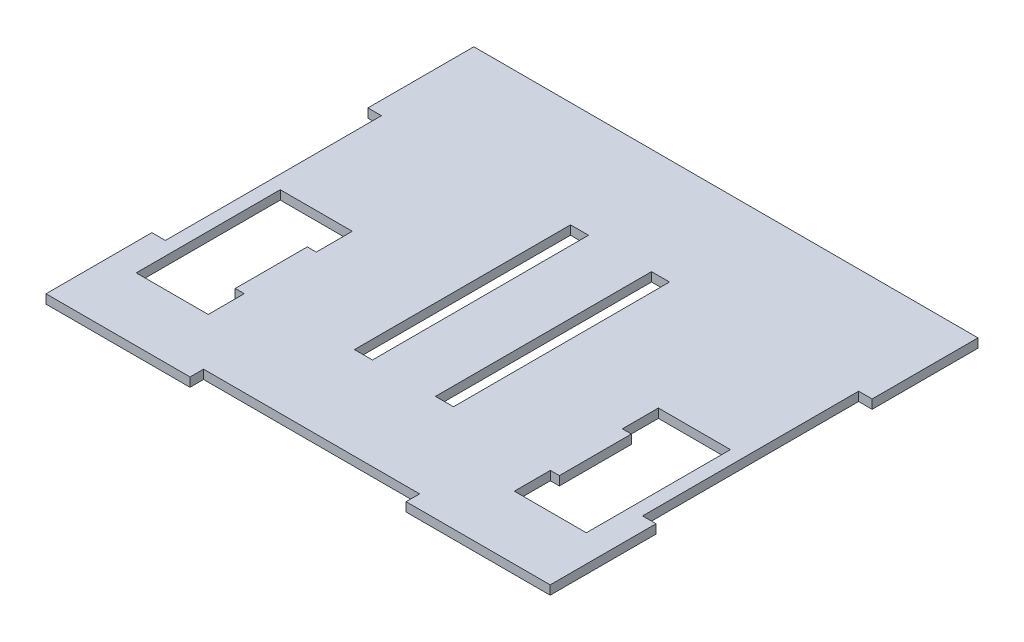
SolidWorks part; units mm, degrees
ref_plane "Front Plane" through (0, 0, 0) normal (0, 0, 1) x (1, 0, 0)
ref_plane "Top Plane" through (0, 0, 0) normal (0, 1, 0) x (1, 0, 0)
ref_plane "Right Plane" through (0, 0, 0) normal (1, 0, 0) x (0, 0, -1)
sketch "Sketch1" plane through (0, 0, 0) normal (0, 1, 0) x (1, 0, 0)
  line L1 (-177.8, -177.8) -> (-76.2, -177.8)
  line L2 (-177.8, -177.8) -> (-177.8, -103.124)
  line L4 (177.8, -177.8) -> (177.8, -103.124)
  line L5 (177.8, 123.952) -> (-177.8, 123.952)
  line L9 (-177.8, 49.276) -> (-168.275, 49.276)
  line L10 (177.8, 49.276) -> (168.275, 49.276)
  line L12 (177.8, -103.124) -> (168.275, -103.124)
  line L13 (168.275, 49.276) -> (168.275, -103.124)
  line L14 (-168.275, 49.276) -> (-168.275, -103.124)
  line L15 (-177.8, -103.124) -> (-168.275, -103.124)
  line L16 (177.8, 49.276) -> (177.8, 123.952)
  line L17 (-177.8, 49.276) -> (-177.8, 123.952)
  line L18 (76.2, -177.8) -> (177.8, -177.8)
  line L20 (76.2, -177.8) -> (76.2, -168.275)
  line L21 (76.2, -168.275) -> (-76.2, -168.275)
  line L22 (-76.2, -177.8) -> (-76.2, -168.275)
  point P0 (0, 0)
  point P16 (168.275, -26.924)
  point P25 (0, -168.275)
  dimension "D3" = 301.752
  dimension "D1" = 152.4
  dimension "D5" = 9.525
  dimension "D6" = 355.6
  dimension "D2" = 150.876
  dimension "D8" = 152.4
  dimension "D9" = 177.8
  dimension "D10" = 9.525
extrude "Boss-Extrude1" add sketch "Sketch1" along normal blind 6.35
sketch "Sketch4" plane through (0, 6.35, 0) normal (0, 1, 0) x (1, 0, 0)
  line L0 (158.75, -133.223) -> (158.75, -31.623)
  line L1 (158.75, -31.623) -> (120.65, -31.623)
  line L2 (120.65, -31.623) -> (120.65, -133.223)
  line L3 (120.65, -133.223) -> (158.75, -133.223)
  line L5 (0, -177.8) -> (0, 177.8) construction
  line L6 (123.952, 177.8) -> (-123.952, 177.8) construction
  line L7 (-120.65, -31.623) -> (-120.65, -133.223)
  line L8 (-158.75, -31.623) -> (-120.65, -31.623)
  line L9 (-158.75, -133.223) -> (-158.75, -31.623)
  line L10 (-120.65, -133.223) -> (-158.75, -133.223)
  dimension "D1" = 101.6
  dimension "D2" = 120.65
  dimension "D3" = 38.1
extrude "Cut-Extrude3" cut sketch "Sketch4" against normal through all
sketch "Sketch5" plane through (0, 6.35, 0) normal (0, 1, 0) x (1, 0, 0)
  line L0 (120.65, -133.223) -> (107.95, -133.223)
  line L1 (107.95, -133.223) -> (107.95, -107.823)
  line L2 (107.95, -107.823) -> (120.65, -107.823)
  line L3 (120.65, -31.623) -> (120.65, -133.223) construction
  line L4 (120.65, -107.823) -> (120.65, -133.223)
  line L5 (177.8, -177.8) -> (-177.8, -177.8) construction
  line L6 (0, -177.8) -> (0, 30.2394) construction
  line L7 (120.65, -31.623) -> (107.95, -31.623)
  line L8 (107.95, -31.623) -> (107.95, -57.023)
  line L9 (107.95, -57.023) -> (120.65, -57.023)
  line L10 (120.65, -57.023) -> (120.65, -31.623)
  line L11 (-107.95, -57.023) -> (-120.65, -57.023)
  line L12 (-107.95, -31.623) -> (-107.95, -57.023)
  line L13 (-120.65, -31.623) -> (-107.95, -31.623)
  line L14 (-120.65, -57.023) -> (-120.65, -31.623)
  line L15 (-107.95, -107.823) -> (-120.65, -107.823)
  line L16 (-107.95, -133.223) -> (-107.95, -107.823)
  line L17 (-120.65, -133.223) -> (-107.95, -133.223)
  line L18 (-120.65, -107.823) -> (-120.65, -133.223)
  dimension "D1" = 25.4
  dimension "D2" = 12.7
  dimension "D3" = 25.4
  dimension "D4" = 12.7
extrude "Cut-Extrude4" cut sketch "Sketch5" against normal through all
sketch "Sketch6" plane through (0, 6.35, 0) normal (0, 1, 0) x (1, 0, 0)
  line L0 (120.65, -107.823) -> (107.95, -107.823) construction
  line L1 (120.65, -57.023) -> (114.3, -57.023)
  line L2 (120.65, -57.023) -> (120.65, -107.823)
  line L3 (120.65, -107.823) -> (114.3, -107.823)
  line L4 (114.3, -57.023) -> (114.3, -107.823)
  line L5 (-120.65, -107.823) -> (-120.65, -57.023) construction
  line L6 (-120.65, -57.023) -> (-114.3, -57.023)
  line L7 (-120.65, -57.023) -> (-120.65, -107.823)
  line L8 (-120.65, -107.823) -> (-114.3, -107.823)
  line L9 (-114.3, -57.023) -> (-114.3, -107.823)
  line L10 (-107.95, -107.823) -> (-120.65, -107.823) construction
extrude "Cut-Extrude5" cut sketch "Sketch6" against normal through all
sketch "Sketch13" plane through (0, 6.35, 0) normal (0, 1, 0) x (1, 0, 0)
  line L0 (-177.8, 49.276) -> (177.8, 49.276) construction
  line L2 (-177.8, -103.124) -> (177.8, -103.124) construction
  line L3 (-34.925, 49.276) -> (-34.925, -103.124)
  line L4 (0, 49.276) -> (0, -103.124) construction
  line L5 (-34.925, 49.276) -> (-22.225, 49.276)
  line L6 (-22.225, 49.276) -> (-22.225, -103.124)
  line L7 (-22.225, -103.124) -> (-34.925, -103.124)
  line L8 (22.225, 49.276) -> (22.225, -103.124)
  line L9 (34.925, 49.276) -> (22.225, 49.276)
  line L10 (34.925, 49.276) -> (34.925, -103.124)
  line L11 (22.225, -103.124) -> (34.925, -103.124)
  dimension "D1" = 12.7
  dimension "D2" = 22.225
extrude "Cut-Extrude8" cut sketch "Sketch13" against normal through all
sketch "Bend-Lines1" [suppressed] plane through (0, 0, 0) normal (0, 1, 0) x (1, 0, 0)
sketch "Bounding-Box1" [suppressed] plane through (0, 0, 0) normal (0, 1, 0) x (1, 0, 0)
equation "\"D2@Sketch1\"=\"D3@Sketch1\"/2"
equation "\"D9@Sketch1\"=\"D6@Sketch1\"/2"
